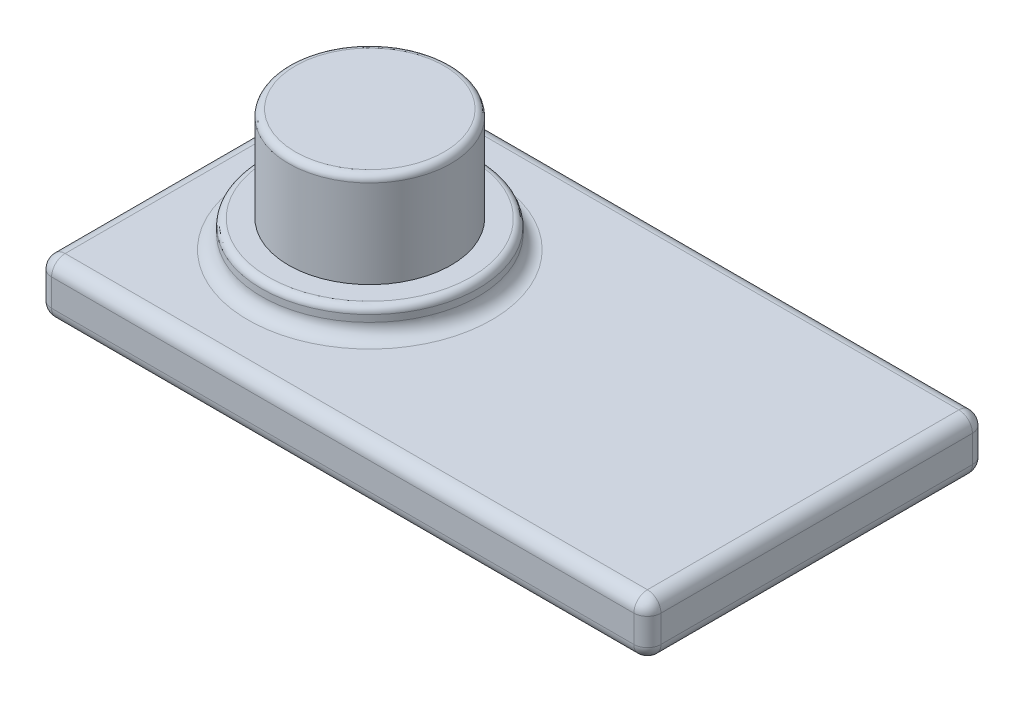
SolidWorks part; units mm, degrees
ref_plane "前视基准面" through (0, 0, 0) normal (0, 0, 1) x (1, 0, 0)
ref_plane "上视基准面" through (0, 0, 0) normal (0, 1, 0) x (1, 0, 0)
ref_plane "右视基准面" through (0, 0, 0) normal (1, 0, 0) x (0, 0, -1)
sketch "草图1" plane through (0, 0, 0) normal (0, 1, 0) x (1, 0, 0)
  line L1 (0, 0) -> (22.5, 0)
  line L2 (0, 0) -> (0, 12.5)
  line L3 (0, 12.5) -> (22.5, 12.5)
  line L4 (22.5, 0) -> (22.5, 12.5)
  dimension "D1" = 22.5
  dimension "D2" = 12.5
extrude "凸台-拉伸1" add sketch "草图1" along normal blind 2
sketch "草图2" plane through (0, 2, 0) normal (0, 1, 0) x (1, 0, 0)
  line L0 (0, 6.25) -> (22.5, 6.25) construction
  line L1 (0, 12.5) -> (0, 0) construction
  line L2 (22.5, 0) -> (22.5, 12.5) construction
  circle A0 centre (6, 6.25) radius 4
  dimension "D1" = 8
  dimension "D2" = 6
extrude "凸台-拉伸2" add sketch "草图2" along normal blind 1
sketch "草图3" plane through (0, 3, 0) normal (0, 1, 0) x (1, 0, 0)
  circle A0 centre (6, 6.25) radius 3
  dimension "D1" = 6
extrude "凸台-拉伸3" add sketch "草图3" along normal blind 3.5
fillet "圆角1" radius 0.5 13 edges at (11.25, 0, 0) (22.5, 0, -6.25) (11.25, 0, -12.5) (0, 0, -6.25) (11.25, 2, -12.5) (22.5, 2, -6.25) (11.25, 2, 0) (0, 2, -6.25) (6, 2, -10.25) (22.5, 1, -12.5) (22.5, 1, 0) (0, 1, 0) (0, 1, -12.5)
fillet "圆角2" radius 0.25 2 edges at (6, 3, -2.25) (6, 6.5, -3.25)
